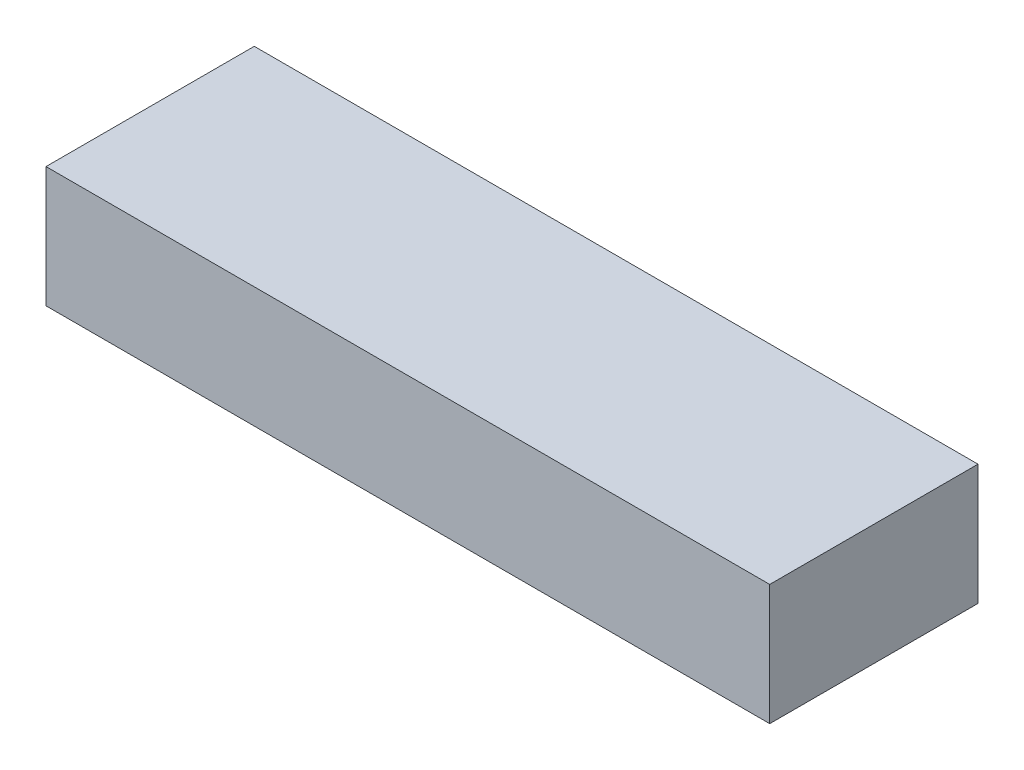
SolidWorks part; units mm, degrees
ref_plane "Front Plane" through (0, 0, 0) normal (0, 0, 1) x (1, 0, 0)
ref_plane "Top Plane" through (0, 0, 0) normal (0, 1, 0) x (1, 0, 0)
ref_plane "Right Plane" through (0, 0, 0) normal (1, 0, 0) x (0, 0, -1)
sketch "Sketch1" plane through (0, 0, 0) normal (0, 1, 0) x (1, 0, 0)
  line L1 (0, 0) -> (18, 0)
  line L2 (0, 0) -> (0, 5.18)
  line L3 (0, 5.18) -> (18, 5.18)
  line L4 (18, 0) -> (18, 5.18)
  dimension "D1" = 18
  dimension "D2" = 5.18
extrude "Boss-Extrude1" add sketch "Sketch1" along normal blind 3
